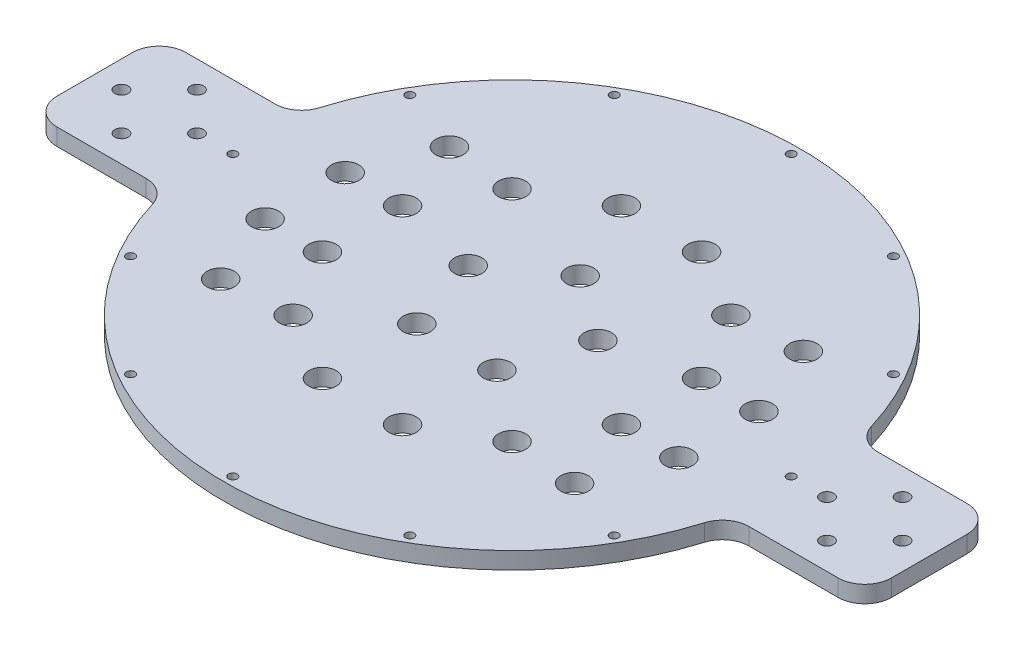
SolidWorks part; units mm, degrees
material "AISI 304"
ref_plane "Front Plane" through (0, 0, 0) normal (0, 0, 1) x (1, 0, 0)
ref_plane "Top Plane" through (0, 0, 0) normal (0, 1, 0) x (1, 0, 0)
ref_plane "Right Plane" through (0, 0, 0) normal (1, 0, 0) x (0, 0, -1)
sketch "Sketch1" plane through (0, 0, 0) normal (0, 1, 0) x (1, 0, 0)
  circle A1 centre (0, 0) radius 107.95
  dimension "D2" = 215.9
extrude "Boss-Extrude1" add sketch "Sketch1" along normal blind 6.35
hole_wizard "M3 Clearance Hole1" positions "Sketch9" profile "Sketch10" hole size "M3" standard "ANSI Metric" end condition through all
sketch "Sketch9" plane through (0, 6.35, 0) normal (0, 1, 0) x (1, 0, 0)
  line L0 (0, 0) -> (0, 104.55) construction
  point P2 (0, 104.55)
  dimension "D1" = 104.55
sketch "Sketch10" plane through (0, 6.35, -104.55) normal (1, 0, 0) x (0, 0, 1)
  line L0 (0, 0) -> (0, 6.35)
  line L1 (0, 6.35) -> (1.6, 6.35)
  line L2 (1.6, 6.35) -> (1.6, 0)
  line L5 (1.6, 0) -> (0, 0)
  line L11 (0, -6.35) -> (0, 107.95) construction
  dimension "Thru Hole Dia." = 3.2
  dimension "Thru Hole Depth" = 6.35
pattern_circular "CirPattern1" count 12 over 360 about axis through (0, 0, 0) along (0, 1, 0) of "M3 Clearance Hole1"
sketch "Sketch2" plane through (0, 0, 0) normal (0, 1, 0) x (1, 0, 0)
  line L0 (-156.2343, 24.1421) -> (-105.2158, 24.1421)
  line L1 (-105.2158, -24.1421) -> (-156.2343, -24.1421)
  line L2 (-156.2343, -24.1421) -> (-156.2343, 24.1421)
  line L3 (-156.2343, 0) -> (0, 0) construction
  line L4 (-146.2343, 0) -> (-132.0921, 14.1421) construction
  line L5 (-132.0921, 14.1421) -> (-117.95, 0) construction
  line L6 (-117.95, 0) -> (-132.0921, -14.1421) construction
  line L7 (-132.0921, -14.1421) -> (-146.2343, 0) construction
  circle A0 centre (0, 0) radius 107.95 construction
  circle A1 centre (0, 0) radius 107.95 construction
  arc A2 (-105.2158, 24.1421) -> (-105.2158, -24.1421) centre (0, 0) ccw
  point P11 (-107.95, 0)
  dimension "D1" = 20
  dimension "D2" = 10
  dimension "D3" = 10
  dimension "D4" = 10
extrude "Boss-Extrude2" add sketch "Sketch2" along normal up to surface (6.35 mm away) up to face at (52.275, 6.35, -88.943)
fillet "Fillet1" radius 10 4 edges at (-105.2158, 3.175, -24.1421) (-156.2343, 3.175, -24.1421) (-156.2343, 3.175, 24.1421) (-105.2158, 3.175, 24.1421)
mirror "Mirror1" about plane through (0, 0, 0) normal (1, 0, 0) of "Boss-Extrude2", "Fillet1"
hole_wizard "#10 Clearance Hole3" positions "Sketch7" profile "Sketch8" hole size "#10" standard "ANSI Inch" end condition through all
sketch "Sketch7" plane through (0, 6.35, 0) normal (0, 1, 0) x (1, 0, 0)
  line L0 (-117.95, 0) -> (-132.0921, -14.1421) construction
  line L1 (-132.0921, -14.1421) -> (-146.2343, 0) construction
  line L2 (-146.2343, 0) -> (-132.0921, 14.1421) construction
  line L3 (-132.0921, 14.1421) -> (-117.95, 0) construction
  line L4 (-117.95, 0) -> (-132.0921, -14.1421) construction
  line L5 (-132.0921, -14.1421) -> (-146.2343, 0) construction
  line L6 (-146.2343, 0) -> (-132.0921, 14.1421) construction
  line L7 (-132.0921, 14.1421) -> (-117.95, 0) construction
  line L8 (0, 107.95) -> (0, -107.95) construction
  line L10 (132.0921, 14.1421) -> (117.95, 0) construction
  line L11 (146.2343, 0) -> (132.0921, 14.1421) construction
  line L12 (132.0921, -14.1421) -> (146.2343, 0) construction
  line L13 (117.95, 0) -> (132.0921, -14.1421) construction
  arc A0 (103.3286, 31.2475) -> (-103.3286, 31.2475) centre (0, 0) ccw construction
  arc A1 (-103.3286, -31.2475) -> (103.3286, -31.2475) centre (0, 0) ccw construction
  point P0 (-132.0921, -14.1421)
  point P2 (-117.95, 0)
  point P4 (-132.0921, 14.1421)
  point P6 (-146.2343, 0)
  point P29 (146.2343, 0)
  point P30 (132.0921, 14.1421)
  point P31 (117.95, 0)
  point P32 (132.0921, -14.1421)
sketch "Sketch8" plane through (-132.0921, 6.35, 14.1421) normal (1, 0, 0) x (0, 0, 1)
  line L0 (0, 0) -> (0, 6.35)
  line L1 (0, 6.35) -> (2.4892, 6.35)
  line L2 (2.4892, 6.35) -> (2.4892, 0)
  line L5 (2.4892, 0) -> (0, 0)
  line L11 (0, -6.35) -> (0, 107.95) construction
  dimension "Thru Hole Dia." = 4.9784
  dimension "Thru Hole Depth" = 6.35
sketch "Sketch11" plane through (0, 6.35, 0) normal (0, 1, 0) x (1, 0, 0)
  line L0 (-88.9, 0) -> (0, 0) construction
  line L1 (0, 0) -> (0, 88.9) construction
  circle A0 centre (0, 0) radius 88.9 construction
  circle A1 centre (-66.2622, 42.8314) radius 5.1
  circle A2 centre (-77.461, 15) radius 5.1
  circle A3 centre (-77.461, -15) radius 5.1
  circle A4 centre (-66.2622, -42.8314) radius 5.1
  circle A9 centre (0, 25.5195) radius 5.1
  circle A10 centre (-24.2705, 7.886) radius 5.1
  circle A11 centre (24.2705, 7.886) radius 5.1
  circle A12 centre (-15, -20.6457) radius 5.1
  circle A13 centre (15, -20.6457) radius 5.1
  circle A14 centre (-55.9808, -15) radius 5.1
  circle A15 centre (-40.9808, -40.9808) radius 5.1
  circle A16 centre (-15, -55.9808) radius 5.1
  circle A17 centre (15, -55.9808) radius 5.1
  circle A18 centre (-55.9808, 15) radius 5.1
  circle A20 centre (55.9808, -15) radius 5.1
  circle A21 centre (40.9808, -40.9808) radius 5.1
  circle A26 centre (0, 0) radius 25.5195 construction
  arc A27 (-64.809, 45) -> (-64.809, -45) centre (0, 0) ccw construction
  circle A28 centre (66.2622, -42.8314) radius 5.1
  circle A29 centre (77.461, -15) radius 5.1
  circle A30 centre (77.461, 15) radius 5.1
  circle A31 centre (66.2622, 42.8314) radius 5.1
  circle A32 centre (0, 0) radius 57.9555 construction
  circle A33 centre (55.9808, 15) radius 5.1
  circle A34 centre (40.9808, 40.9808) radius 5.1
  circle A35 centre (15, 55.9808) radius 5.1
  circle A36 centre (-15, 55.9808) radius 5.1
  circle A37 centre (-40.9808, 40.9808) radius 5.1
  dimension "D1" = 177.8
  dimension "D2" = 10.2
  dimension "D3" = 30
  dimension "D8" = 10
  dimension "D9" = 90
  dimension "D11" = 30
  dimension "D4" = 30
  dimension "D5" = 30
  dimension "D6" = 30
  dimension "D7" = 30
  dimension "D10" = 30
  dimension "D12" = 30
  dimension "D13" = 30
  dimension "D14" = 30
  dimension "D15" = 30
  dimension "D16" = 30
  dimension "D17" = 30
  dimension "D18" = 30
  dimension "D19" = 30
extrude "Cut-Extrude1" cut sketch "Sketch11" against normal up to next (6.35 mm away)
